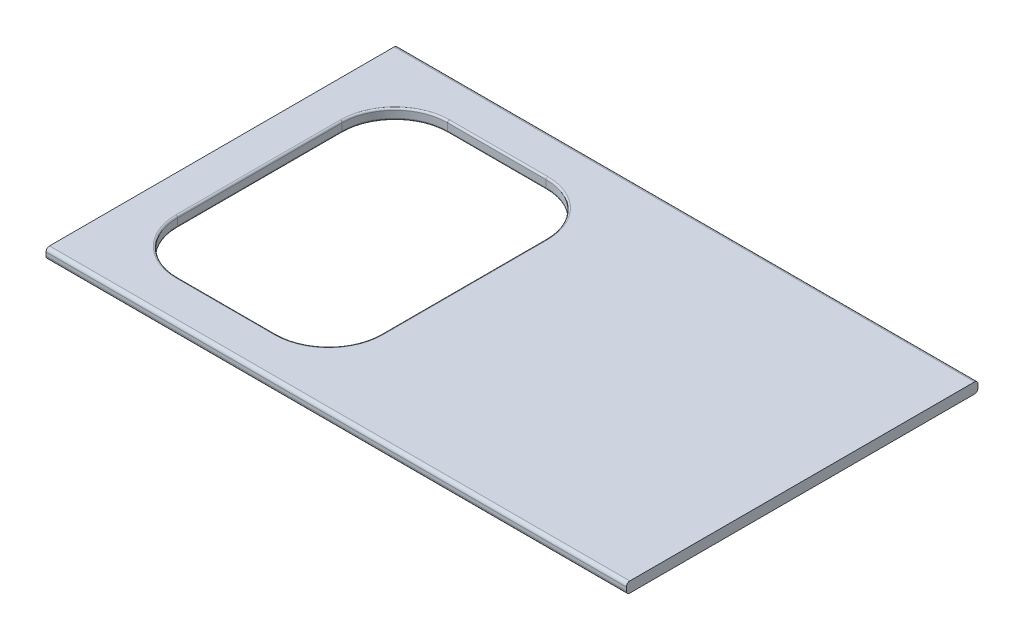
SolidWorks part; units mm, degrees
ref_plane "前视基准面" through (0, 0, 0) normal (0, 0, 1) x (1, 0, 0)
ref_plane "上视基准面" through (0, 0, 0) normal (0, 1, 0) x (1, 0, 0)
ref_plane "右视基准面" through (0, 0, 0) normal (1, 0, 0) x (0, 0, -1)
other "Configuration Table"
sketch "草图1" plane through (0, 0, 0) normal (0, 1, 0) x (1, 0, 0)
  line L1 (-82.5, -50) -> (82.5, -50)
  line L2 (-82.5, -50) -> (-82.5, 50)
  line L3 (-82.5, 50) -> (82.5, 50)
  line L4 (82.5, -50) -> (82.5, 50)
  line L5 (-82.5, -50) -> (82.5, 50) construction
  line L6 (-82.5, 50) -> (82.5, -50) construction
  point P0 (0, 0)
  dimension "D1" = 100
  dimension "D2" = 165
extrude "凸台-拉伸1" add sketch "草图1" along normal blind 3
sketch "草图2" plane through (0, 0, 0) normal (0, -1, 0) x (1, 0, 0)
  line L1 (-71.6888, 38.4115) -> (-13.7194, 38.4115)
  line L2 (-71.6888, 38.4115) -> (-71.6888, -38.4115)
  line L3 (-71.6888, -38.4115) -> (-13.7194, -38.4115)
  line L4 (-13.7194, 38.4115) -> (-13.7194, -38.4115)
  line L5 (-71.6888, 38.4115) -> (-13.7194, -38.4115) construction
  line L6 (-71.6888, -38.4115) -> (-13.7194, 38.4115) construction
  point P0 (-42.7041, 0)
extrude "切除-拉伸1" cut sketch "草图2" against normal through all
fillet "圆角1" radius 15 4 edges at (-71.6888, 1.5, -38.4115) (-71.6888, 1.5, 38.4115) (-13.7194, 1.5, -38.4115) (-13.7194, 1.5, 38.4115)
fillet "圆角2" radius 1 4 edges at (0, 3, -50) (0, 0, -50) (0, 3, 50) (0, 0, 50)
fillet "圆角3" radius 0.5 16 edges at (-67.2954, 3, 34.0181) (-42.7041, 3, 38.4115) (-18.1127, 3, 34.0181) (-13.7194, 3, 0) (-18.1127, 3, -34.0181) (-42.7041, 3, -38.4115) (-67.2954, 3, -34.0181) (-67.2954, 0, 34.0181) (-42.7041, 0, 38.4115) (-18.1127, 0, 34.0181) (-13.7194, 0, 0) (-18.1127, 0, -34.0181) (-42.7041, 0, -38.4115) (-67.2954, 0, -34.0181) (-71.6888, 3, 0) (-71.6888, 0, 0)
